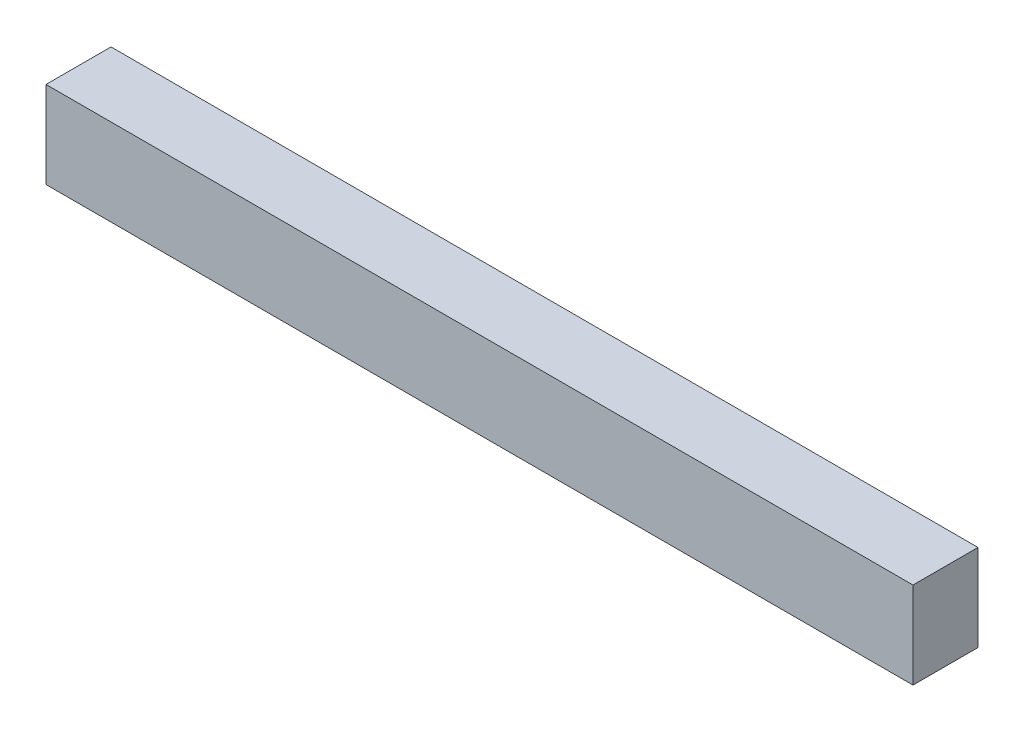
SolidWorks part; units mm, degrees
ref_plane "Front Plane" through (0, 0, 0) normal (0, 0, 1) x (1, 0, 0)
ref_plane "Top Plane" through (0, 0, 0) normal (0, 1, 0) x (1, 0, 0)
ref_plane "Right Plane" through (0, 0, 0) normal (1, 0, 0) x (0, 0, -1)
sketch "Sketch1" plane through (0, 0, 0) normal (0, 1, 0) x (1, 0, 0)
  line L1 (0, 0) -> (40, 0)
  line L2 (0, 0) -> (0, 3)
  line L3 (0, 3) -> (40, 3)
  line L4 (40, 0) -> (40, 3)
  dimension "D1" = 40
  dimension "D2" = 3
extrude "Boss-Extrude1" add sketch "Sketch1" along normal blind 4
